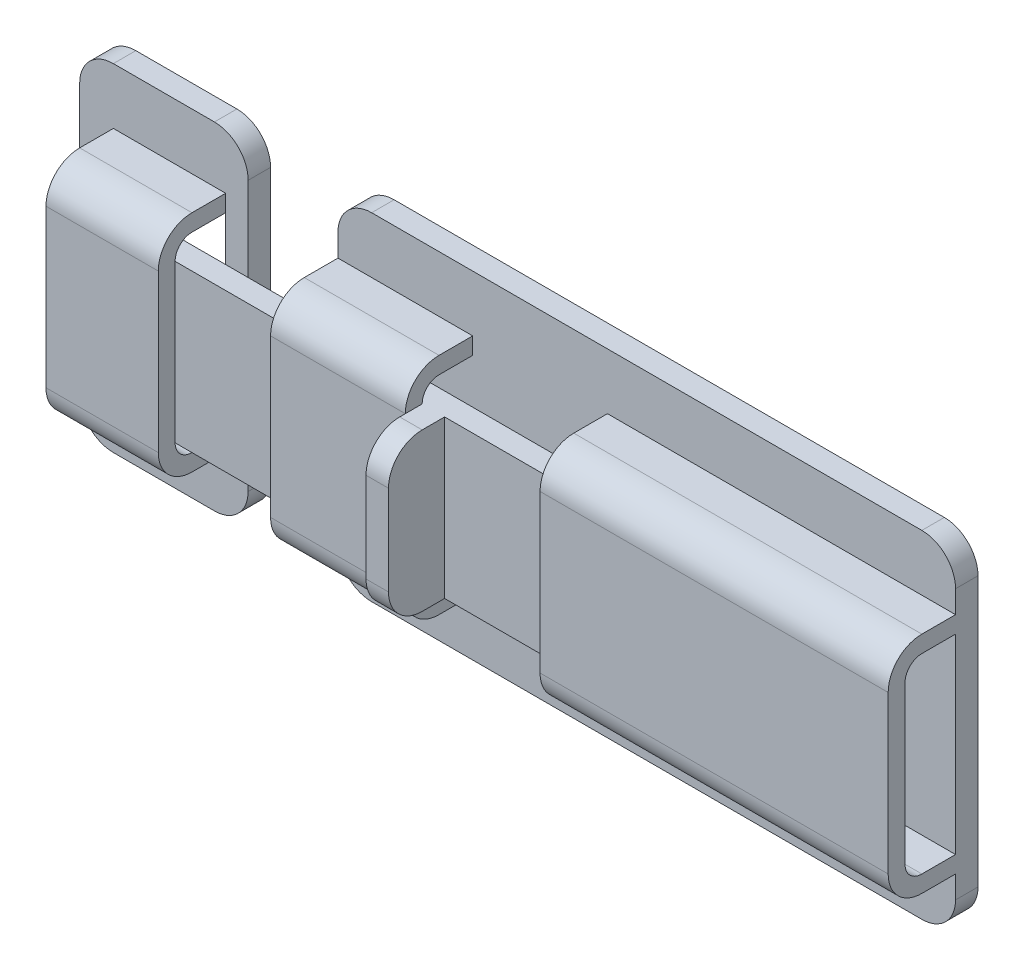
SolidWorks part; units mm, degrees
ref_plane "前视基准面" through (0, 0, 0) normal (0, 0, 1) x (1, 0, 0)
ref_plane "上视基准面" through (0, 0, 0) normal (0, 1, 0) x (1, 0, 0)
ref_plane "右视基准面" through (0, 0, 0) normal (1, 0, 0) x (0, 0, -1)
sketch "草图1" plane through (0, 0, 0) normal (0, 0, 1) x (1, 0, 0)
  line L1 (-7.5, -15) -> (7.5, -15)
  line L2 (-7.5, -15) -> (-7.5, 15)
  line L3 (-7.5, 15) -> (7.5, 15)
  line L4 (7.5, -15) -> (7.5, 15)
  line L5 (-7.5, -15) -> (7.5, 15) construction
  line L6 (-7.5, 15) -> (7.5, -15) construction
  point P0 (0, 0)
  dimension "D1" = 30
  dimension "D2" = 15
extrude "凸台-拉伸1" add sketch "草图1" along normal blind 2
ref_plane "基准面1" through (5.5, 0, 0) normal (1, 0, 0) x (0, 0, -1)
sketch "草图2" plane through (5.5, 0, 0) normal (1, 0, 0) x (0, 0, -1)
  line L0 (-2, -15) -> (-2, 15) construction
  line L1 (-2, 10) -> (-8, 10)
  line L2 (-2, 10) -> (-2, 8.5)
  line L3 (-2, -10) -> (-8, -10)
  line L4 (-8, 10) -> (-8, -10)
  line L5 (0, 0) -> (-7.9406, 0) construction
  line L6 (-2, 8.5) -> (-6.5, 8.5)
  line L7 (-6.5, 8.5) -> (-6.5, -8.5)
  line L8 (-6.5, -8.5) -> (-2, -8.5)
  line L9 (-2, -8.5) -> (-2, -10)
  dimension "D1" = 20
  dimension "D2" = 6
  dimension "D3" = 1.5
  dimension "D4" = 1.5
  dimension "D5" = 1.5
extrude "凸台-拉伸2" add sketch "草图2" against normal blind 10
fillet "圆角1" radius 1.5 2 edges at (0.5, -8.5, 6.5) (0.5, 8.5, 6.5)
sketch "草图3" plane through (0, 0, 0) normal (0, 0, -1) x (-1, 0, 0)
  line L0 (-5.5, -7) -> (-5.5, 7) construction
  line L1 (4.5, -7) -> (4.5, 7) construction
  line L2 (4.5, 8.5) -> (-5.5, 8.5) construction
  line L3 (4.5, -8.5) -> (-5.5, -8.5) construction
  line L4 (-5.5, -8.5) -> (-5.5, 8.5)
  line L5 (4.5, -8.5) -> (4.5, 8.5)
  line L6 (4.5, 8.5) -> (-5.5, 8.5)
  line L7 (4.5, -8.5) -> (-5.5, -8.5)
extrude "切除-拉伸1" cut sketch "草图3" against normal blind 3
sketch "草图4" plane through (0, 0, 2) normal (0, 0, 1) x (1, 0, 0)
  line L0 (7.5, 15) -> (-7.5, 15) construction
  line L1 (15.5, 15) -> (70.5, 15)
  line L2 (15.5, 15) -> (15.5, -15)
  line L3 (15.5, -15) -> (70.5, -15)
  line L4 (70.5, 15) -> (70.5, -15)
  line L5 (-7.5, -15) -> (7.5, -15) construction
  line L6 (7.5, -15) -> (7.5, 15) construction
  dimension "D1" = 8
  dimension "D2" = 55
extrude "凸台-拉伸3" add sketch "草图4" against normal blind 2 separate body
sketch "草图5" plane through (0, 0, 6.5) normal (0, 0, -1) x (-1, 0, 0)
  line L0 (4.5, 7) -> (-5.5, 7) construction
  line L1 (2.5, 7) -> (-44.5, 7)
  line L2 (2.5, 7) -> (2.5, -7)
  line L3 (2.5, -7) -> (-44.5, -7)
  line L4 (-44.5, 7) -> (-44.5, -7)
  line L5 (-7.5, -15) -> (-7.5, 15) construction
  line L6 (-5.5, -7) -> (4.5, -7) construction
  dimension "D1" = 47
  dimension "D2" = 10
extrude "凸台-拉伸4" add sketch "草图5" along normal blind 2
sketch "草图6" plane through (0, -7, 0) normal (0, -1, 0) x (1, 0, 0)
  line L0 (44.5, 6.5) -> (5.5, 6.5) construction
  line L1 (27.5, 6.5) -> (29.5, 6.5)
  line L2 (27.5, 6.5) -> (27.5, 11.5)
  line L3 (27.5, 11.5) -> (29.5, 11.5)
  line L4 (29.5, 6.5) -> (29.5, 11.5)
  line L5 (44.5, 4.5) -> (44.5, 6.5) construction
  dimension "D1" = 2
  dimension "D2" = 15
  dimension "D3" = 5
extrude "凸台-拉伸5" add sketch "草图6" against normal up to surface (14 mm away) up to face at (17.9, 7, 5.7)
sketch "草图7" plane through (15.5, 0, 0) normal (-1, 0, 0) x (0, 0, 1)
  line L0 (6.5, -7) -> (6.5, 7) construction
  line L1 (6.5, -7) -> (6.5, 7)
  line L8 (2, 10) -> (8, 10) construction
  line L9 (5, 8.5) -> (2, 8.5) construction
  line L11 (8, 10) -> (8, -10) construction
  line L12 (2, -8.5) -> (5, -8.5) construction
  line L13 (8, -10) -> (2, -10) construction
  line L14 (5, 8.5) -> (2, 8.5)
  line L15 (2, -8.5) -> (5, -8.5)
  line L16 (2, 10) -> (8, 10)
  line L17 (8, 10) -> (8, -10)
  line L18 (8, -10) -> (2, -10)
  line L19 (2, 10) -> (2, 8.5)
  line L20 (2, -10) -> (2, -8.5)
  arc A1 (6.5, 7) -> (5, 8.5) centre (5, 7) ccw construction
  arc A3 (5, -8.5) -> (6.5, -7) centre (5, -7) ccw construction
  arc A5 (6.5, 7) -> (5, 8.5) centre (5, 7) ccw
  arc A7 (5, -8.5) -> (6.5, -7) centre (5, -7) ccw
extrude "凸台-拉伸6" add sketch "草图7" against normal blind 12
ref_plane "基准面2" through (39.5, 0, 0) normal (1, 0, 0) x (0, 0, -1)
sketch "草图8" plane through (39.5, 0, 0) normal (1, 0, 0) x (0, 0, -1)
  line L3 (-6.5, 7) -> (-6.5, -7) construction
  line L8 (-2, 10) -> (-2, 8.5) construction
  line L9 (-8, 10) -> (-2, 10) construction
  line L10 (-2, 8.5) -> (-5, 8.5) construction
  line L11 (-6.5, 7) -> (-6.5, -7)
  line L12 (-8, -10) -> (-8, 10) construction
  line L13 (-5, -8.5) -> (-2, -8.5) construction
  line L14 (-2, -10) -> (-8, -10) construction
  line L15 (-2, -8.5) -> (-2, -10) construction
  line L16 (-8, 10) -> (-2, 10)
  line L17 (-8, -10) -> (-8, 10)
  line L18 (-2, -10) -> (-8, -10)
  line L19 (-2, 10) -> (-2, 8.5)
  line L20 (-2, 8.5) -> (-5, 8.5)
  line L21 (-5, -8.5) -> (-2, -8.5)
  line L22 (-2, -8.5) -> (-2, -10)
  arc A1 (-5, 8.5) -> (-6.5, 7) centre (-5, 7) ccw construction
  arc A3 (-6.5, -7) -> (-5, -8.5) centre (-5, -7) ccw construction
  arc A5 (-5, 8.5) -> (-6.5, 7) centre (-5, 7) ccw
  arc A7 (-6.5, -7) -> (-5, -8.5) centre (-5, -7) ccw
extrude "凸台-拉伸7" add sketch "草图8" along normal up to surface (31 mm away) up to face at (70.5, 0, 1)
fillet "圆角4" radius 3 16 edges at (-7.5, -15, 1) (-7.5, 15, 1) (7.5, 15, 1) (15.5, 15, 1) (70.5, 15, 1) (7.5, -15, 1) (15.5, -15, 1) (70.5, -15, 1) (28.5, -7, 11.5) (28.5, 7, 11.5) (55, 10, 8) (55, -10, 8) (21.5, -10, 8) (21.5, 10, 8) (0.5, -10, 8) (0.5, 10, 8)
